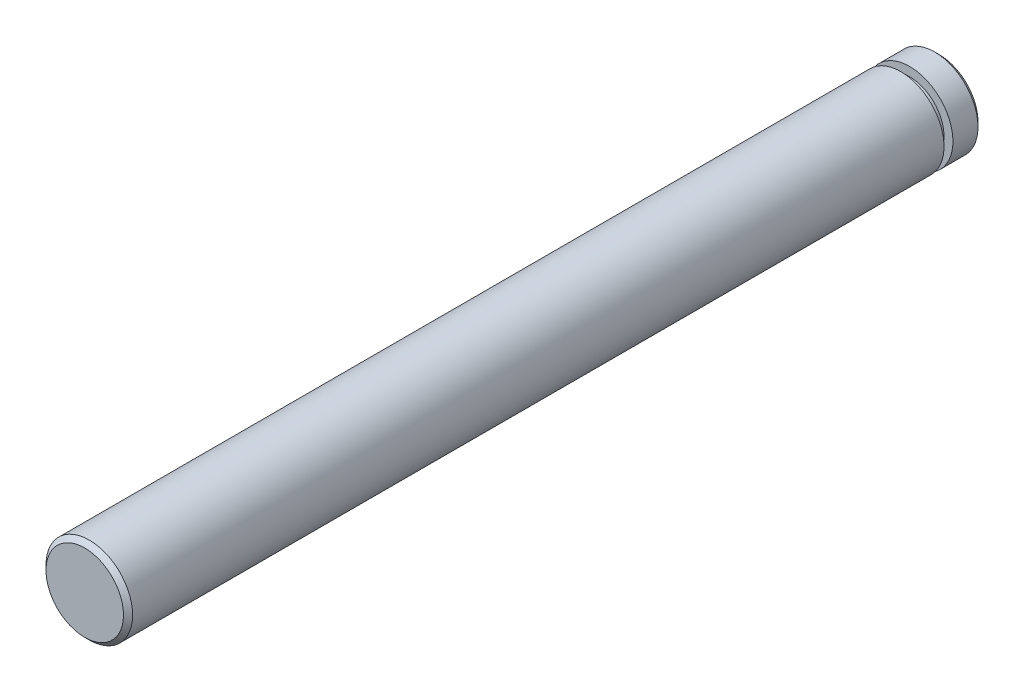
SolidWorks part; units mm, degrees
ref_plane "Front Plane" through (0, 0, 0) normal (0, 0, 1) x (1, 0, 0)
ref_plane "Top Plane" through (0, 0, 0) normal (0, 1, 0) x (1, 0, 0)
ref_plane "Right Plane" through (0, 0, 0) normal (1, 0, 0) x (0, 0, -1)
sketch "Sketch1" plane through (0, 0, 0) normal (0, 0, 1) x (1, 0, 0)
  circle A0 centre (0, 0) radius 4.826
  dimension "D1" = 9.652
extrude "Boss-Extrude1" add sketch "Sketch1" along normal blind 95.25
chamfer "Chamfer1" distance 0.508 angle 45 2 edges at (4.826, 0, 0) (4.826, 0, 95.25)
sketch "Sketch4" plane through (0, 0, 0) normal (1, 0, 0) x (0, 0, -1)
  line L0 (0, -4.318) -> (0, 4.318) construction
  line L1 (-3.302, 4.826) -> (-4.2926, 4.826)
  line L2 (-3.302, 4.826) -> (-3.302, 3.8354)
  line L3 (-3.302, 3.8354) -> (-4.2926, 3.8354)
  line L4 (-4.2926, 4.826) -> (-4.2926, 3.8354)
  line L5 (-0.508, 4.826) -> (-94.742, 4.826) construction
  line L6 (20.8151, 0) -> (-101.9839, 0) construction
  dimension "D1" = 0.9906
  dimension "D2" = 0.9906
  dimension "D3" = 3.302
  dimension "D4" = 0
revolve "Cut-Revolve1" cut sketch "Sketch4" angle 360 about L6
